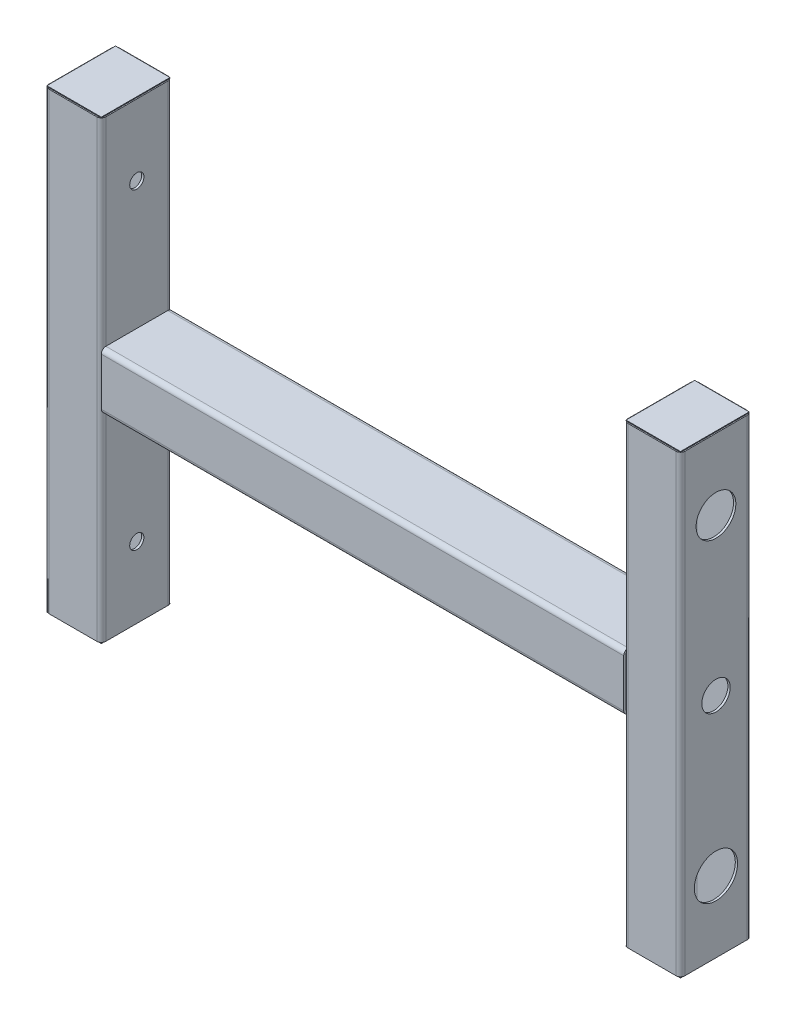
SolidWorks part; units mm, degrees
material "Q235A"
ref_plane "前视" through (0, 0, 0) normal (0, 0, 1) x (1, 0, 0)
ref_plane "上视" through (0, 0, 0) normal (0, 1, 0) x (1, 0, 0)
ref_plane "右视" through (0, 0, 0) normal (1, 0, 0) x (0, 0, -1)
sketch "草图1" plane through (0, 0, 0) normal (0, 0, 1) x (1, 0, 0)
  line L0 (-1020, 800) -> (-1020, -800)
  line L1 (-1020, 0) -> (1020, 0)
  line L2 (1020, 800) -> (1020, -800)
  dimension "D1" = 2040
  dimension "D2" = 1600
other "结构构件1"
ref_plane "基准面1" through (-1020, 800, 0) normal (0, -1, 0) x (1, 0, 0)
sketch "Sketch1" plane through (-1020, 800, 0) normal (0, -1, 0) x (1, 0, 0)
  line L0 (-84, -117) -> (84, -117)
  line L1 (-92, -109) -> (-92, 109)
  line L2 (84, 117) -> (-84, 117)
  line L3 (92, 109) -> (92, -109)
  line L4 (-84, -125) -> (84, -125)
  line L5 (-100, -109) -> (-100, 109)
  line L6 (84, 125) -> (-84, 125)
  line L7 (100, 109) -> (100, -109)
  arc A0 (100, 109) -> (84, 125) centre (84, 109) ccw
  arc A1 (84, -125) -> (100, -109) centre (84, -109) ccw
  arc A2 (-100, -109) -> (-84, -125) centre (-84, -109) ccw
  arc A3 (-84, 125) -> (-100, 109) centre (-84, 109) ccw
  arc A4 (-84, 117) -> (-92, 109) centre (-84, 109) ccw
  arc A5 (92, 109) -> (84, 117) centre (84, 109) ccw
  arc A6 (84, -117) -> (92, -109) centre (84, -109) ccw
  arc A7 (-92, -109) -> (-84, -117) centre (-84, -109) ccw
  point P0 (0, 125)
  point P1 (100, 0)
  point P2 (0, -125)
  point P3 (-100, 0)
  point P4 (-100, 125)
  point P5 (100, 125)
  point P6 (100, -125)
  point P7 (-100, -125)
  point P8 (0, 0)
  point P33 (0, 0)
  dimension "D1" = 16
  dimension "Thickness" = 8
  dimension "V_leg" = 250
  dimension "H_leg" = 200
other "结构构件2"
ref_plane "基准面2" through (-1020, 0, 0) normal (1, 0, 0) x (0, 1, 0)
sketch "Sketch11" plane through (-1020, 0, 0) normal (1, 0, 0) x (0, 1, 0)
  line L0 (-84, -117) -> (84, -117)
  line L1 (-92, -109) -> (-92, 109)
  line L2 (84, 117) -> (-84, 117)
  line L3 (92, 109) -> (92, -109)
  line L4 (-84, -125) -> (84, -125)
  line L5 (-100, -109) -> (-100, 109)
  line L6 (84, 125) -> (-84, 125)
  line L7 (100, 109) -> (100, -109)
  arc A0 (100, 109) -> (84, 125) centre (84, 109) ccw
  arc A1 (84, -125) -> (100, -109) centre (84, -109) ccw
  arc A2 (-100, -109) -> (-84, -125) centre (-84, -109) ccw
  arc A3 (-84, 125) -> (-100, 109) centre (-84, 109) ccw
  arc A4 (-84, 117) -> (-92, 109) centre (-84, 109) ccw
  arc A5 (92, 109) -> (84, 117) centre (84, 109) ccw
  arc A6 (84, -117) -> (92, -109) centre (84, -109) ccw
  arc A7 (-92, -109) -> (-84, -117) centre (-84, -109) ccw
  point P0 (0, 125)
  point P1 (100, 0)
  point P2 (0, -125)
  point P3 (-100, 0)
  point P4 (-100, 125)
  point P5 (100, 125)
  point P6 (100, -125)
  point P7 (-100, -125)
  point P8 (0, 0)
  point P33 (0, 0)
  dimension "D1" = 16
  dimension "Thickness" = 8
  dimension "V_leg" = 250
  dimension "H_leg" = 200
other "剪裁/延伸1"
sketch "草图2" plane through (1120, 0, 0) normal (1, 0, 0) x (0, 0, -1)
  line L0 (0, 800) -> (0, -800) construction
  circle A0 centre (0, 550) radius 70
  circle A1 centre (0, -550) radius 76.128
  dimension "D3" = 140
  dimension "D1" = 550
  dimension "D2" = 550
extrude "切除-拉伸1" cut sketch "草图2" against normal up to surface (200 mm away) up to face at (920, 0, 0)
sketch "草图3" plane through (1120, 0, 0) normal (1, 0, 0) x (0, 0, -1)
  circle A0 centre (0, 0) radius 50
  dimension "D1" = 100
extrude "切除-拉伸2" cut sketch "草图3" against normal through all
other "顶端盖1" parameters "D1"=3, "D2"=3, "D3"=3
sketch "草图4" plane through (-1120, 0, 0) normal (-1, 0, 0) x (0, 0, 1)
  circle A0 centre (0, 550) radius 70
  circle A1 centre (0, 550) radius 25
  circle A2 centre (0, -550) radius 76.128
  circle A3 centre (0, -550) radius 25
  dimension "D1" = 140
  dimension "D2" = 50
  dimension "D3" = 50
sketch "草图5" plane through (-1120, 0, 0) normal (-1, 0, 0) x (0, 0, 1)
  circle A0 centre (0, 550) radius 25
  circle A1 centre (0, -550) radius 25
  dimension "D1" = 50
  dimension "D2" = 50
extrude "切除-拉伸3" cut sketch "草图5" against normal up to surface (200 mm away) up to face at (-920, 0, 50)
